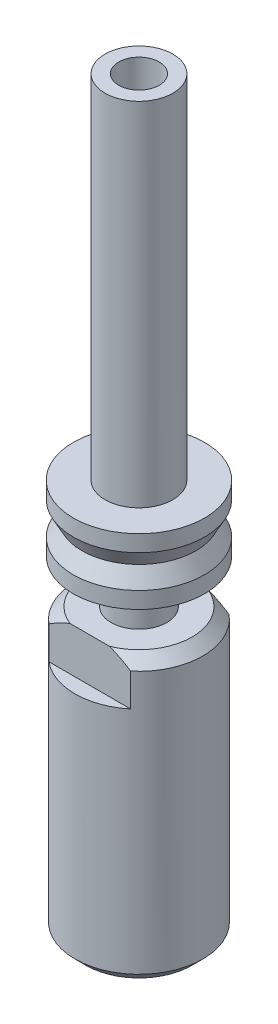
SolidWorks part; units mm, degrees
ref_plane "Front" through (0, 0, 0) normal (0, 0, 1) x (1, 0, 0)
ref_plane "Top" through (0, 0, 0) normal (0, 1, 0) x (1, 0, 0)
ref_plane "Right" through (0, 0, 0) normal (1, 0, 0) x (0, 0, -1)
sketch "Sketch1" plane through (0, 0, 0) normal (1, 0, 0) x (0, 0, -1)
  line L0 (0, 26.0943) -> (0, 0) construction
  line L1 (0, 0) -> (25.1321, 0) construction
  line L2 (0.925, 24.1) -> (0.925, -15)
  line L3 (0.925, -15) -> (2.925, -15)
  line L4 (2.925, -15) -> (2.925, -2)
  line L5 (2.925, -2) -> (1.275, -2)
  line L6 (1.275, -2) -> (1.275, 0)
  line L7 (1.275, 0) -> (3, 0)
  line L8 (3, 0) -> (3, 0.753)
  line L9 (3, 3) -> (1.55, 3)
  line L10 (1.55, 3) -> (1.55, 24.1)
  line L11 (1.55, 24.1) -> (0.925, 24.1)
  line L12 (3, 2.247) -> (2.6, 1.5)
  line L13 (2.6, 1.5) -> (3, 0.753)
  line L14 (3, 2.247) -> (3, 3)
  dimension "D1" = 15
  dimension "D2" = 2
  dimension "D3" = 1.85
  dimension "D4" = 5.85
  dimension "D5" = 3.1
  dimension "D6" = 2.55
  dimension "D7" = 24.1
  dimension "D8" = 6
  dimension "D9" = 5.2
  dimension "D10" = 0.753
  dimension "D11" = 3
revolve "Revolve1" add sketch "Sketch1" angle 360 about L0
cosmetic thread "Cosmetic Thread1" parameters "D2"=4.11
chamfer "Chamfer1" distance 0.5 angle 45 2 edges at (0, -15, 2.925) (0, -2, 2.925)
sketch "Sketch2" plane through (0, 0, 0) normal (1, 0, 0) x (0, 0, -1)
  line L0 (0, 0) -> (0, -5.7203) construction
  line L2 (-4.25, -2) -> (-2.25, -2)
  line L3 (-4.25, -2) -> (-4.25, -4)
  line L4 (-4.25, -4) -> (-2.25, -4)
  line L5 (-2.25, -2) -> (-2.25, -4)
  line L6 (2.425, -2) -> (-2.425, -2) construction
  line L7 (4.25, -2) -> (4.25, -4)
  line L8 (4.25, -4) -> (2.25, -4)
  line L9 (2.25, -2) -> (2.25, -4)
  line L10 (4.25, -2) -> (2.25, -2)
  dimension "D1" = 4.5
  dimension "D2" = 2
  dimension "D3" = 2
extrude "Cut-Extrude1" cut sketch "Sketch2" against normal mid plane 6
sketch "Sketch3" plane through (0, 0, 0) normal (1, 0, 0) x (0, 0, -1)
  line L0 (-1.275, 0) -> (1.275, 0) construction
  line L1 (-3, 24.1) -> (3, 24.1)
  line L2 (-3, 24.1) -> (-3, 19.1)
  line L3 (-3, 19.1) -> (3, 19.1)
  line L4 (3, 24.1) -> (3, 19.1)
  line L5 (1.55, 24.1) -> (-1.55, 24.1) construction
  line L6 (3, 2.247) -> (3, 3) construction
  line L7 (-3, 3) -> (-3, 2.247) construction
  dimension "D1" = 19.1
extrude "Cut-Extrude2" cut sketch "Sketch3" against normal mid plane 6
